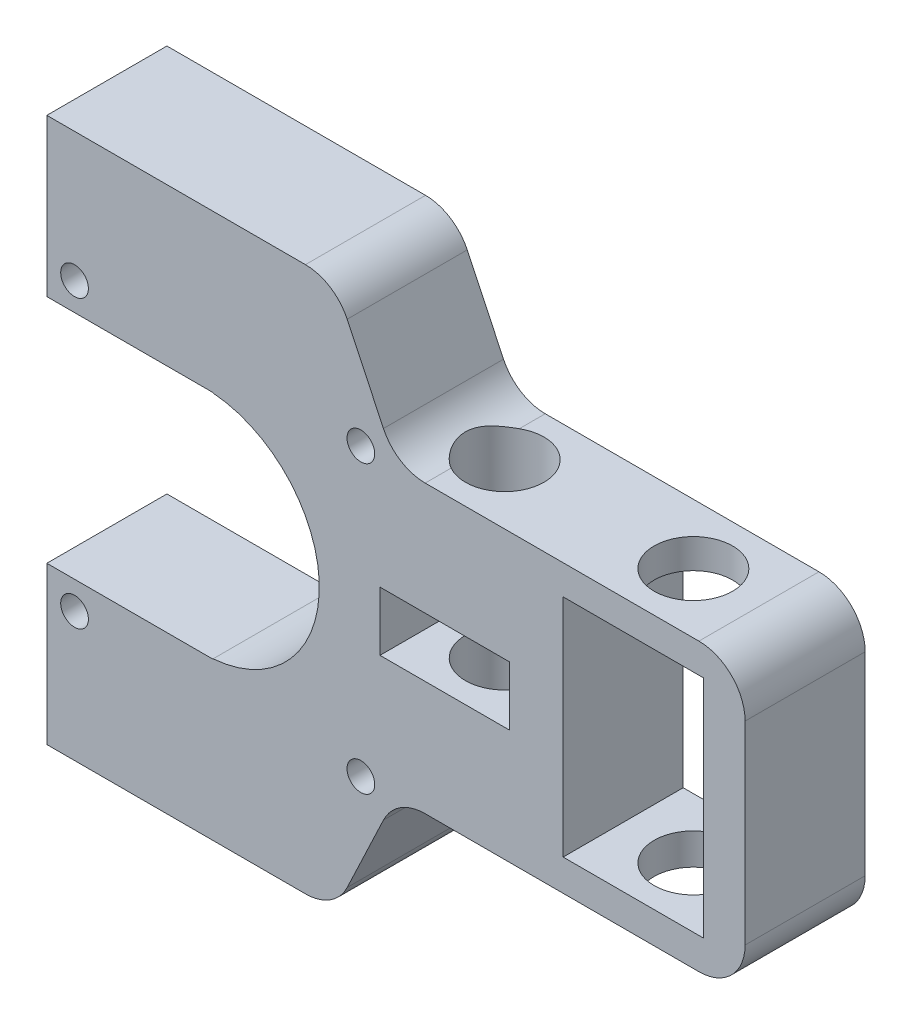
SolidWorks part; units mm, degrees
ref_plane "Alzado" through (0, 0, 0) normal (0, 0, 1) x (1, 0, 0)
ref_plane "Planta" through (0, 0, 0) normal (0, 1, 0) x (1, 0, 0)
ref_plane "Vista lateral" through (0, 0, 0) normal (1, 0, 0) x (0, 0, -1)
sketch "Croquis2" plane through (0, 0, 0) normal (0, 0, 1) x (1, 0, 0)
  line L0 (22.1337, 16.3063) -> (22.1337, -14.4937) construction
  line L1 (-41.3663, 19.3063) -> (-41.3663, -17.6937)
  line L2 (-41.3663, 19.3063) -> (-41.3663, 30.3063)
  line L3 (-41.3663, 30.3063) -> (-13.3663, 30.3063)
  line L4 (-8.8483, 27.4481) -> (-4.9213, 19.1644)
  line L5 (-41.3663, 30.3063) -> (-41.3663, 19.3063)
  line L6 (-41.3663, -17.6937) -> (-41.3663, 19.3063)
  line L10 (34.2337, 0.8063) -> (-41.3663, 0.8063) construction
  line L11 (34.2337, 16.3063) -> (-41.3663, 16.3063) construction
  line L12 (34.2337, -14.6937) -> (-41.3663, -14.6937) construction
  line L14 (1.7037, 16.3063) -> (1.7037, -14.4937) construction
  line L15 (-0.4033, 16.3063) -> (29.2337, 16.3063)
  line L16 (14.5337, -11.2937) -> (29.7337, -11.2937)
  line L17 (14.5337, -11.2937) -> (14.5337, 13.1063)
  line L18 (14.5337, 13.1063) -> (29.7337, 13.1063)
  line L19 (29.7337, -11.2937) -> (29.7337, 13.1063)
  line L20 (14.5337, -11.2937) -> (29.7337, 13.1063) construction
  line L21 (14.5337, 13.1063) -> (29.7337, -11.2937) construction
  line L22 (-5.2963, -2.2937) -> (8.7037, -2.2937)
  line L23 (-5.2963, -2.2937) -> (-5.2963, 4.1063)
  line L24 (-5.2963, 4.1063) -> (8.7037, 4.1063)
  line L25 (8.7037, -2.2937) -> (8.7037, 4.1063)
  line L26 (-5.2963, -2.2937) -> (8.7037, 4.1063) construction
  line L27 (-5.2963, 4.1063) -> (8.7037, -2.2937) construction
  line L28 (34.2337, 11.3063) -> (34.2337, -9.6937)
  line L29 (29.2337, -14.6937) -> (-0.4033, -14.6937)
  line L30 (-4.9213, -17.5519) -> (-8.8483, -25.8356)
  line L31 (-13.3663, -28.6937) -> (-41.3663, -28.6937)
  line L32 (-41.3663, -28.6937) -> (-41.3663, -17.6937)
  circle A0 centre (-38.3663, 16.3063) radius 1.5
  circle A1 centre (-7.3663, 16.3063) radius 1.5
  circle A2 centre (-7.3663, -14.6937) radius 1.5
  circle A3 centre (-38.3663, -14.6937) radius 1.5
  circle A4 centre (-24.3663, 0.8063) radius 12.5
  arc A5 (-8.8483, 27.4481) -> (-13.3663, 30.3063) centre (-13.3663, 25.3063) ccw
  arc A6 (-13.3663, -28.6937) -> (-8.8483, -25.8356) centre (-13.3663, -23.6937) ccw
  arc A7 (29.2337, 16.3063) -> (34.2337, 11.3063) centre (29.2337, 11.3063) cw
  arc A8 (34.2337, -9.6937) -> (29.2337, -14.6937) centre (29.2337, -9.6937) cw
  arc A9 (-0.4033, 16.3063) -> (-4.9213, 19.1644) centre (-0.4033, 21.3063) cw
  arc A10 (-0.4033, -14.6937) -> (-4.9213, -17.5519) centre (-0.4033, -19.6937) ccw
  point P0 (-22.8663, 0.8063)
  point P9 (-38.3663, 16.3063)
  point P10 (-38.3663, -14.6937)
  point P11 (-39.8663, -14.6937)
  point P12 (-7.3663, -14.6937)
  point P13 (-7.3663, 16.3063)
  point P34 (22.1337, 0.9063)
  point P39 (1.7037, 0.9063)
  point P58 (-3.5663, 16.3063)
  point P61 (-3.5663, -14.6937)
  dimension "D6" = 3
  dimension "D7" = 25
  dimension "D2" = 5
  dimension "D8" = 5
  dimension "D14" = 5
  dimension "D15" = 5
  dimension "D19" = 5
  dimension "D20" = 5
  dimension "D3" = 31
  dimension "D4" = 15.5
  dimension "D5" = 15.5
  dimension "D9" = 20.43
  dimension "D10" = 24.4
  dimension "D11" = 15.2
  dimension "D12" = 6.4
  dimension "D13" = 14
  dimension "D16" = 11
  dimension "D17" = 11
  dimension "D18" = 4.5
  dimension "D21" = 28
  dimension "D22" = 28
  dimension "D23" = 31
  dimension "D24" = 3
  dimension "D25" = 3
extrude "Saliente-Extruir1" add sketch "Croquis2" along normal blind 13
sketch "Croquis3" plane through (-41.3663, 0, 0) normal (-1, 0, 0) x (0, 0, 1)
  line L4 (6.5, 23.8063) -> (6.5, -22.1937) construction
  line L5 (0, -28.6937) -> (0, 30.3063) construction
  circle A0 centre (6.5, 23.8063) radius 4
  circle A1 centre (6.5, -22.1937) radius 4
  point P6 (6.5, 0.8063)
  point P7 (0, 0.8063)
  dimension "D1" = 8
  dimension "D2" = 6.5
  dimension "D4" = 46
extrude "Cortar-Extruir1" cut sketch "Croquis3" against normal blind 30
sketch "Croquis4" plane through (-41.3663, 0, 0) normal (-1, 0, 0) x (0, 0, 1)
  line L0 (6.5, 30.3063) -> (6.5, -28.6937) construction
  line L4 (13, 30.3063) -> (0, 30.3063) construction
  line L5 (13, -28.6937) -> (0, -28.6937) construction
  line L6 (13, -28.6937) -> (13, 30.3063) construction
  line L8 (0, -11.6937) -> (13, -11.6937)
  line L9 (0, -11.6937) -> (0, 13.3063)
  line L10 (0, 13.3063) -> (13, 13.3063)
  line L11 (13, -11.6937) -> (13, 13.3063)
  line L12 (0, -11.6937) -> (13, 13.3063) construction
  line L13 (0, 13.3063) -> (13, -11.6937) construction
  point P6 (6.5, 0.8063)
  dimension "D1" = 25
extrude "Cortar-Extruir2" cut sketch "Croquis4" against normal blind 18
sketch "Croquis5" plane through (0, 16.3063, 0) normal (0, 1, 0) x (1, 0, 0)
  line L0 (34.2337, -13) -> (34.2337, 0) construction
  circle A0 centre (22.1337, -6.5) radius 4.25
  circle A1 centre (1.7037, -6.5) radius 4.25
  dimension "D3" = 8.5
  dimension "D1" = 12.1
  dimension "D2" = 20.43
extrude "Cortar-Extruir3" cut sketch "Croquis5" against normal through all and the other way through all
